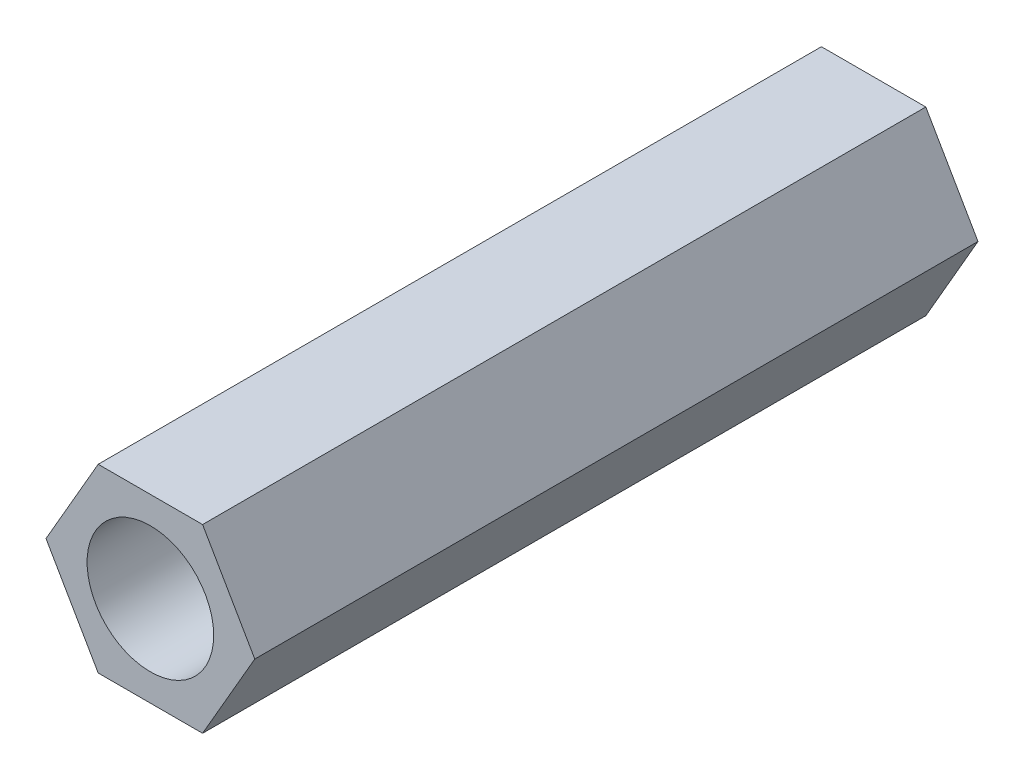
SolidWorks part; units mm, degrees
ref_plane "Front Plane" through (0, 0, 0) normal (0, 0, 1) x (1, 0, 0)
ref_plane "Top Plane" through (0, 0, 0) normal (0, 1, 0) x (1, 0, 0)
ref_plane "Right Plane" through (0, 0, 0) normal (1, 0, 0) x (0, 0, -1)
sketch "Sketch1" plane through (0, 0, 0) normal (0, 0, 1) x (1, 0, 0)
  line L1 (5.7735, 0) -> (2.8868, 5)
  line L2 (2.8868, 5) -> (-2.8868, 5)
  line L3 (-2.8868, 5) -> (-5.7735, 0)
  line L4 (-5.7735, 0) -> (-2.8868, -5)
  line L5 (-2.8868, -5) -> (2.8868, -5)
  line L6 (2.8868, -5) -> (5.7735, 0)
  circle A0 centre (0, 0) radius 5 construction
  dimension "D1" = 10
extrude "Boss-Extrude1" add sketch "Sketch1" along normal blind 40
sketch "Sketch2" plane through (0, 0, 40) normal (0, 0, 1) x (1, 0, 0)
  circle A0 centre (0, 0) radius 3.5
  dimension "D1" = 7
extrude "Cut-Extrude1" cut sketch "Sketch2" against normal blind 15
hole_wizard "Ø8.0 (8) Diameter Hole1" positions "Sketch3" profile "Sketch5" hole size "Ø8.0" standard "ANSI Metric"
sketch "Sketch3" plane through (0, 0, 0) normal (0, 0, -1) x (-1, 0, 0)
  point P0 (0, 0)
sketch "Sketch5" plane through (0, 0, 0) normal (1, 0, 0) x (0, 1, 0)
  line L0 (0, 0) -> (0, 17.4034)
  line L1 (0, 17.4034) -> (4, 15)
  line L2 (4, 15) -> (4, 0)
  line L5 (4, 0) -> (0, 0)
  line L10 (0, 17.4034) -> (-4, 15) construction
  line L11 (0, -6.35) -> (0, 107.95) construction
  dimension "Hole Dia." = 8
  dimension "Hole Depth" = 15
  dimension "Drill Angle" = 118
